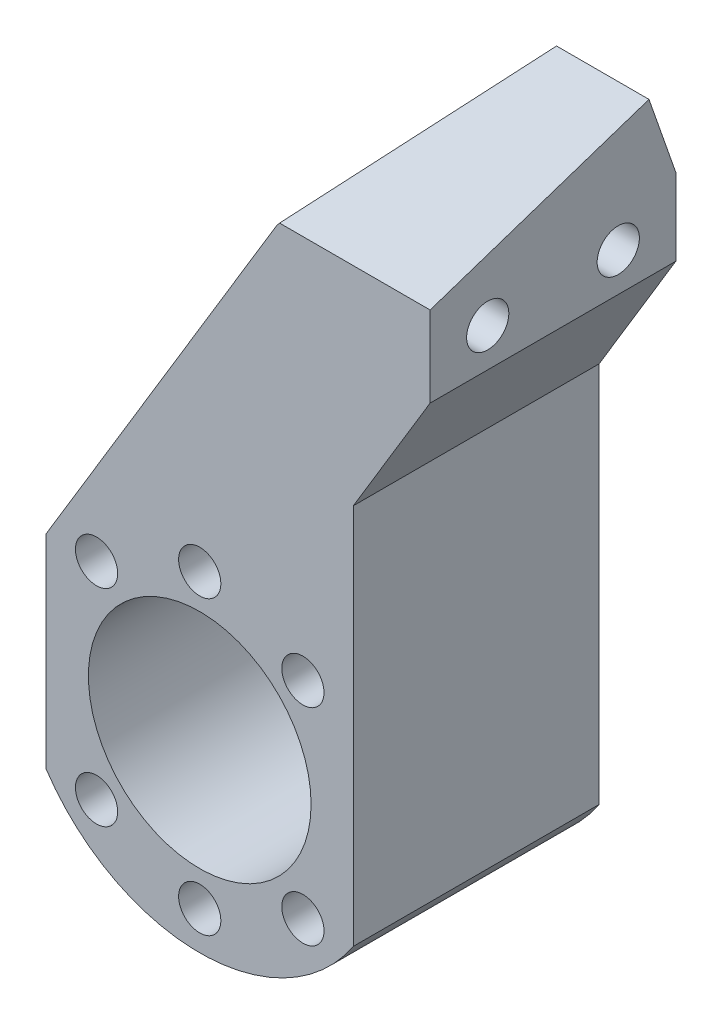
SolidWorks part; units mm, degrees
ref_plane "Plan de face" through (0, 0, 0) normal (0, 0, 1) x (1, 0, 0)
ref_plane "Plan de dessus" through (0, 0, 0) normal (0, 1, 0) x (1, 0, 0)
ref_plane "Plan de droite" through (0, 0, 0) normal (1, 0, 0) x (0, 0, -1)
sketch "Esquisse2" plane through (0, 0, 0) normal (0, 0, 1) x (1, 0, 0)
  line L0 (20, 13.2665) -> (20, -13.2665)
  line L1 (-20, 13.2665) -> (-20, -13.2665)
  line L2 (-20, 0) -> (20, 0) construction
  arc A2 (-20, 13.2665) -> (20, 13.2665) centre (0, 0) cw
  arc A3 (-20, -13.2665) -> (20, -13.2665) centre (0, 0) ccw
  circle A4 centre (0, 0) radius 19 construction
  circle A5 centre (0, 19) radius 2.75
  circle A6 centre (-13.435, 13.435) radius 2.75
  circle A7 centre (13.435, 13.435) radius 2.75
  circle A8 centre (0, -19) radius 2.75
  circle A9 centre (13.435, -13.435) radius 2.75
  circle A10 centre (-13.435, -13.435) radius 2.75
  circle A11 centre (0, 0) radius 14.5
  point P4 (0, 0)
  point P8 (0, 0)
  point P10 (-20, 0)
  point P11 (20, 0)
  dimension "D2" = 24
  dimension "D3" = 38
  dimension "D4" = 5.5
  dimension "D5" = 29
  dimension "D1" = 40
  dimension "D6" = 45
  dimension "D7" = 45
  dimension "D8" = 45
  dimension "D9" = 45
extrude "Boss.-Extru.1" add sketch "Esquisse2" along normal blind 32
sketch "Esquisse7" plane through (0, 0, 0) normal (0, 0, -1) x (-1, 0, 0)
  line L2 (-10, 63.001) -> (20, 13.2665)
  line L3 (-10, 63.001) -> (-30, 63.001)
  line L4 (-30, 63.001) -> (-30, 53.001)
  line L6 (-20, 13.2665) -> (-20, 36.4228)
  line L7 (-20, 36.4228) -> (-30, 53.001)
  arc A0 (20, 13.2665) -> (-20, 13.2665) centre (0, 0) ccw construction
  arc A1 (20, 13.2665) -> (-20, 13.2665) centre (0, 0) ccw
  dimension "D1" = 39.7345
  dimension "D2" = 10
  dimension "D3" = 10
  dimension "D4" = 20
extrude "Boss.-Extru.4" add sketch "Esquisse7" against normal up to surface (32 mm away) up to face at (0, 0, 32)
sketch "Esquisse10" plane through (30, 0, 0) normal (1, 0, 0) x (0, 0, -1)
  line L0 (-32, 53.001) -> (-32, 63.001) construction
  line L1 (-24.5, 58.001) -> (-7.5, 58.001) construction
  line L2 (-32, 63.001) -> (0, 63.001) construction
  circle A0 centre (-24.5, 58.001) radius 2.75
  circle A1 centre (-7.5, 58.001) radius 2.75
  point P4 (-16, 58.001)
  point P7 (-32, 58.001)
  point P10 (-16, 63.001)
  dimension "D1" = 5.5
  dimension "D2" = 7.5
extrude "Enlèv. mat.-Extru.3" cut sketch "Esquisse10" against normal up to next
sketch "Esquisse11" plane through (30, 0, 0) normal (1, 0, 0) x (0, 0, -1)
  line L0 (-32, 63.001) -> (0, 63.001)
  line L4 (0, 63.001) -> (-3.5, 73.001)
  line L5 (-32, 63.001) -> (-32, 63.501)
  line L6 (-32, 63.501) -> (-3.5, 73.001)
  dimension "D1" = 10
  dimension "D2" = 3.5
  dimension "D3" = 0.5
extrude "Boss.-Extru.6" add sketch "Esquisse11" against normal up to vertex (20 mm away)
sketch "Esquisse12" plane through (0, 0, 0) normal (0, 0, -1) x (-1, 0, 0)
  line L0 (-10, 63.001) -> (-17.9628, 73.001)
  line L1 (-10, 63.001) -> (-10, 73.001) construction
  line L4 (-10, 63.001) -> (-10, 73.001)
  line L6 (-17.9628, 73.001) -> (-10, 73.001)
  line L7 (-10, 73.001) -> (-30, 73.001) construction
extrude "Enlèv. mat.-Extru.4" cut sketch "Esquisse12" against normal up to next
ref_plane "Plan1" through (20, 0, 0) normal (1, 0, 0) x (0, 0, -1)
sketch "Esquisse13" plane through (20, 0, 0) normal (1, 0, 0) x (0, 0, -1)
  circle A0 centre (-7.5, 58.001) radius 6
  circle A1 centre (-24.5, 58.001) radius 6
  dimension "D1" = 12
extrude "Enlèv. mat.-Extru.5" cut sketch "Esquisse13" against normal up to next
